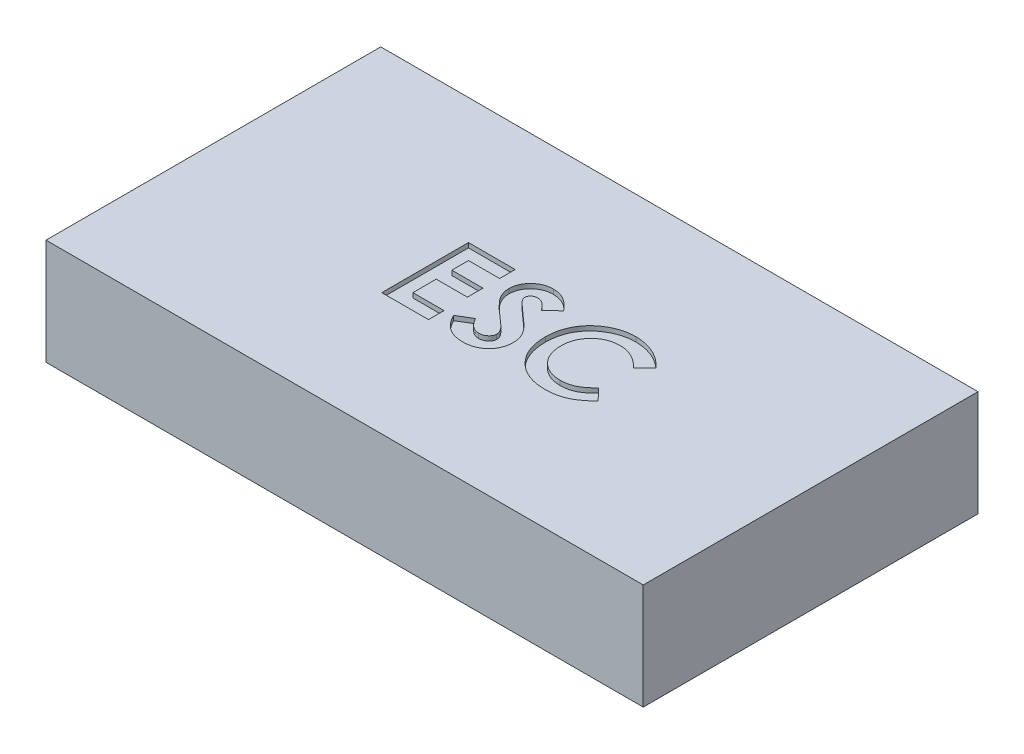
SolidWorks part; units mm, degrees
ref_plane "Front Plane" through (0, 0, 0) normal (0, 0, 1) x (1, 0, 0)
ref_plane "Top Plane" through (0, 0, 0) normal (0, 1, 0) x (1, 0, 0)
ref_plane "Right Plane" through (0, 0, 0) normal (1, 0, 0) x (0, 0, -1)
sketch "Sketch1" plane through (0, 0, 0) normal (0, 1, 0) x (1, 0, 0)
  line L1 (-51.65, -28.95) -> (51.65, -28.95)
  line L2 (-51.65, -28.95) -> (-51.65, 28.95)
  line L3 (-51.65, 28.95) -> (51.65, 28.95)
  line L4 (51.65, -28.95) -> (51.65, 28.95)
  line L5 (0, 28.95) -> (0, -28.95) construction
  line L6 (-51.65, 0) -> (51.65, 0) construction
  point P0 (0, 0)
  dimension "D1" = 57.9
  dimension "D2" = 103.3
extrude "Boss-Extrude1" add sketch "Sketch1" along normal blind 18.3
sketch "Sketch2" plane through (0, 18.3, 0) normal (0, 1, 0) x (1, 0, 0)
  text T0 "<b>ESC</b>\r\n" font "Century Gothic" height 15
extrude "Cut-Extrude1" cut sketch "Sketch2" against normal blind 0.8
